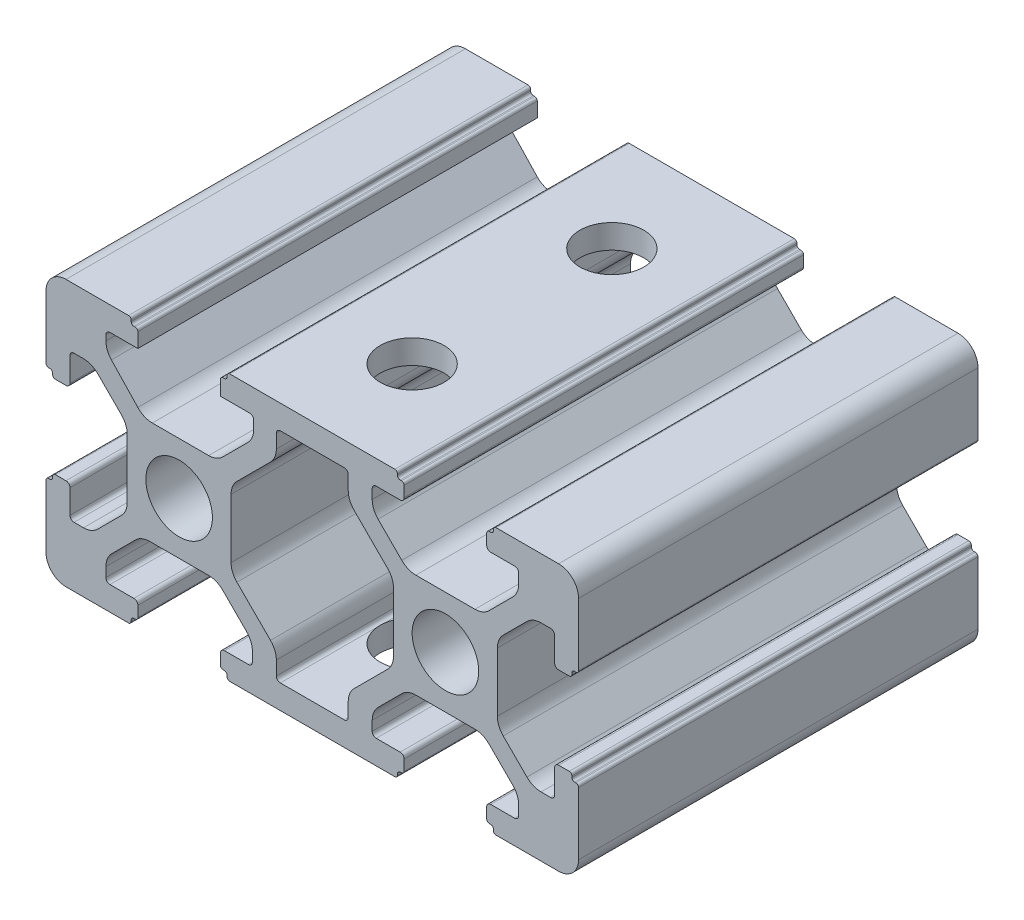
SolidWorks part; units mm, degrees
material "6063-O"
ref_plane "Front Plane" through (0, 0, 0) normal (0, 0, 1) x (1, 0, 0)
ref_plane "Top Plane" through (0, 0, 0) normal (0, 1, 0) x (1, 0, 0)
ref_plane "Right Plane" through (0, 0, 0) normal (1, 0, 0) x (0, 0, -1)
sketch "Sketch1" plane through (0, 0, 0) normal (0, 0, 1) x (1, 0, 0)
  line L0 (1.5, 0) -> (6.2, 0)
  line L1 (40, 1.5) -> (40, 6.2)
  line L2 (38.5, 20) -> (33.8, 20)
  line L3 (0, 18.5) -> (0, 13.8)
  line L4 (17.6, 1.8) -> (22.4, 1.8)
  line L5 (32.218, 13.9) -> (27.782, 13.9)
  line L6 (26.1, 12.218) -> (26.1, 7.782)
  line L7 (17.6, 18.2) -> (22.4, 18.2)
  line L8 (12.218, 13.9) -> (7.9864, 13.9)
  line L9 (6.1, 12.218) -> (6.1, 7.782)
  line L10 (7.782, 6.1) -> (12.218, 6.1)
  line L11 (13.9, 7.782) -> (13.9, 12.218)
  line L12 (27.782, 6.1) -> (32.218, 6.1)
  line L13 (33.9, 7.782) -> (33.9, 12.218)
  line L14 (26.7213, 14.3393) -> (24.9393, 16.1213)
  line L15 (33.2787, 14.3393) -> (35.0607, 16.1213)
  line L16 (34.3393, 13.2787) -> (36.1213, 15.0607)
  line L17 (25.6607, 6.7213) -> (23.1393, 4.2)
  line L18 (15.2, 1.8) -> (13.4, 1.8)
  line L19 (26.7213, 5.6607) -> (24.9393, 3.8787)
  line L20 (24.8, 1.8) -> (26.6, 1.8)
  line L21 (15.3, 18.2) -> (13.1, 18.2)
  line L22 (13.2787, 14.3393) -> (15.1607, 16.2213)
  line L23 (14.3393, 13.2787) -> (16.8607, 15.8)
  line L24 (5.6607, 6.7213) -> (3.8787, 4.9393)
  line L25 (6.7213, 5.6607) -> (4.9393, 3.8787)
  line L26 (6.897, 14.3689) -> (4.9106, 16.4674)
  line L27 (5.6607, 13.2787) -> (3.8787, 15.0607)
  line L28 (14.3393, 6.7213) -> (16.8607, 4.2)
  line L29 (13.2787, 5.6607) -> (15.0607, 3.8787)
  line L30 (24.8, 18.2) -> (26.6, 18.2)
  line L31 (25.6607, 13.2787) -> (23.1393, 15.8)
  line L32 (34.3393, 6.7213) -> (36.1213, 4.9393)
  line L33 (33.2787, 5.6607) -> (35.0607, 3.8787)
  line L34 (1.8, 15.2) -> (1.8, 13.4)
  line L35 (24.5, 2.1) -> (24.5, 2.818)
  line L36 (4.5, 2.1) -> (4.5, 2.818)
  line L37 (2.818, 4.5) -> (2.1, 4.5)
  line L38 (4.5, 17.9) -> (4.5, 17.4986)
  line L39 (2.818, 15.5) -> (2.1, 15.5)
  line L40 (15.6, 17.9) -> (15.6, 17.282)
  line L41 (15.5, 2.818) -> (15.5, 2.1)
  line L42 (38.2, 15.2) -> (38.2, 13.4)
  line L43 (35.5, 2.818) -> (35.5, 2.1)
  line L44 (37.182, 4.5) -> (37.9, 4.5)
  line L45 (35.5, 17.182) -> (35.5, 17.9)
  line L46 (37.182, 15.5) -> (37.9, 15.5)
  line L47 (17.3, 2.1) -> (17.3, 3.1393)
  line L48 (22.7, 2.1) -> (22.7, 3.1393)
  line L49 (17.3, 17.9) -> (17.3, 16.8607)
  line L50 (22.7, 17.9) -> (22.7, 16.8607)
  line L51 (24.5, 17.9) -> (24.5, 17.182)
  line L52 (6.9, 19.3) -> (6.9, 18.2)
  line L53 (13.1, 19.3) -> (13.1, 18.2)
  line L54 (6.9, 1.5) -> (6.9, 0.7)
  line L55 (13.1, 1.5) -> (13.1, 0.7)
  line L56 (13.8, 0) -> (26.2, 0)
  line L57 (6.6, 1.8) -> (4.8, 1.8)
  line L58 (6.9, 18.2) -> (4.8, 18.2)
  line L59 (6.2, 20) -> (1.5, 20)
  line L60 (39.3, 6.9) -> (38.5, 6.9)
  line L61 (39.3, 13.1) -> (38.5, 13.1)
  line L62 (1.5, 13.1) -> (0.7, 13.1)
  line L63 (1.5, 6.9) -> (0.7, 6.9)
  line L64 (0, 6.2) -> (0, 1.5)
  line L65 (1.8, 6.6) -> (1.8, 4.8)
  line L66 (38.2, 6.6) -> (38.2, 4.8)
  line L67 (40, 13.8) -> (40, 18.5)
  line L68 (33.1, 19.3) -> (33.1, 18.5)
  line L69 (26.9, 19.3) -> (26.9, 18.5)
  line L70 (26.9, 1.5) -> (26.9, 0.7)
  line L71 (33.1, 1.5) -> (33.1, 0.7)
  line L72 (33.8, 0) -> (38.5, 0)
  line L73 (33.4, 1.8) -> (35.2, 1.8)
  line L74 (26.2, 20) -> (13.8, 20)
  line L75 (33.4, 18.2) -> (35.2, 18.2)
  line L76 (6.7, 0.5) -> (6.6, 0.5)
  line L77 (6.4, 0.3) -> (6.4, 0.2)
  line L78 (13.3, 0.5) -> (13.4, 0.5)
  line L79 (13.6, 0.3) -> (13.6, 0.2)
  line L80 (26.7, 0.5) -> (26.6, 0.5)
  line L81 (26.4, 0.3) -> (26.4, 0.2)
  line L82 (33.3, 0.5) -> (33.4, 0.5)
  line L83 (33.6, 0.3) -> (33.6, 0.2)
  line L85 (6.4, 19.8) -> (6.4, 19.7)
  line L86 (6.6, 19.5) -> (6.7, 19.5)
  line L87 (13.6, 19.8) -> (13.6, 19.7)
  line L88 (13.4, 19.5) -> (13.3, 19.5)
  line L89 (26.4, 19.8) -> (26.4, 19.7)
  line L90 (26.6, 19.5) -> (26.7, 19.5)
  line L91 (33.6, 19.8) -> (33.6, 19.7)
  line L92 (33.4, 19.5) -> (33.3, 19.5)
  line L93 (0.5, 13.3) -> (0.5, 13.4)
  line L94 (0.3, 13.6) -> (0.2, 13.6)
  line L95 (0.5, 6.7) -> (0.5, 6.6)
  line L96 (0.3, 6.4) -> (0.2, 6.4)
  line L97 (39.5, 13.3) -> (39.5, 13.4)
  line L98 (39.7, 13.6) -> (39.8, 13.6)
  line L99 (39.5, 6.7) -> (39.5, 6.6)
  line L100 (39.7, 6.4) -> (39.8, 6.4)
  circle A0 centre (10, 10) radius 2.5
  circle A1 centre (30, 10) radius 2.5
  arc A2 (38.5, 0) -> (40, 1.5) centre (38.5, 1.5) ccw
  arc A3 (40, 18.5) -> (38.5, 20) centre (38.5, 18.5) ccw
  arc A4 (1.5, 0) -> (0, 1.5) centre (1.5, 1.5) cw
  arc A5 (1.5, 20) -> (0, 18.5) centre (1.5, 18.5) ccw
  arc A6 (26.7213, 5.6607) -> (27.782, 6.1) centre (27.782, 4.6) cw
  arc A7 (32.218, 6.1) -> (33.2787, 5.6607) centre (32.218, 4.6) cw
  arc A8 (33.9, 7.782) -> (34.3393, 6.7213) centre (35.4, 7.782) ccw
  arc A9 (33.2787, 14.3393) -> (32.218, 13.9) centre (32.218, 15.4) cw
  arc A10 (14.3393, 6.7213) -> (13.9, 7.782) centre (15.4, 7.782) cw
  arc A11 (14.3393, 13.2787) -> (13.9, 12.218) centre (15.4, 12.218) ccw
  arc A12 (25.6607, 6.7213) -> (26.1, 7.782) centre (24.6, 7.782) ccw
  arc A13 (26.1, 12.218) -> (25.6607, 13.2787) centre (24.6, 12.218) ccw
  arc A14 (27.782, 13.9) -> (26.7213, 14.3393) centre (27.782, 15.4) cw
  arc A15 (5.6607, 13.2787) -> (6.1, 12.218) centre (4.6, 12.218) cw
  arc A16 (5.6607, 6.7213) -> (6.1, 7.782) centre (4.6, 7.782) ccw
  arc A17 (13.2787, 5.6607) -> (12.218, 6.1) centre (12.218, 4.6) ccw
  arc A18 (6.7213, 5.6607) -> (7.782, 6.1) centre (7.782, 4.6) cw
  arc A19 (13.2787, 14.3393) -> (12.218, 13.9) centre (12.218, 15.4) cw
  arc A20 (6.897, 14.3689) -> (7.9864, 13.9) centre (7.9864, 15.4) ccw
  arc A21 (36.1213, 4.9393) -> (37.182, 4.5) centre (37.182, 6) ccw
  arc A22 (36.1213, 15.0607) -> (37.182, 15.5) centre (37.182, 14) cw
  arc A23 (35.0607, 16.1213) -> (35.5, 17.182) centre (34, 17.182) ccw
  arc A24 (24.5, 17.182) -> (24.9393, 16.1213) centre (26, 17.182) ccw
  arc A25 (22.7, 16.8607) -> (23.1393, 15.8) centre (24.2, 16.8607) ccw
  arc A26 (17.3, 16.8607) -> (16.8607, 15.8) centre (15.8, 16.8607) cw
  arc A27 (4.9106, 16.4674) -> (4.5, 17.4986) centre (6, 17.4986) cw
  arc A28 (15.6, 17.282) -> (15.1607, 16.2213) centre (14.1, 17.282) cw
  arc A29 (3.8787, 15.0607) -> (2.818, 15.5) centre (2.818, 14) ccw
  arc A30 (3.8787, 4.9393) -> (2.818, 4.5) centre (2.818, 6) cw
  arc A31 (4.9393, 3.8787) -> (4.5, 2.818) centre (6, 2.818) ccw
  arc A32 (35.0607, 3.8787) -> (35.5, 2.818) centre (34, 2.818) cw
  arc A33 (24.9393, 3.8787) -> (24.5, 2.818) centre (26, 2.818) ccw
  arc A34 (22.7, 3.1393) -> (23.1393, 4.2) centre (24.2, 3.1393) cw
  arc A35 (17.3, 3.1393) -> (16.8607, 4.2) centre (15.8, 3.1393) ccw
  arc A36 (15.5, 2.818) -> (15.0607, 3.8787) centre (14, 2.818) ccw
  arc A37 (1.8, 6.6) -> (1.5, 6.9) centre (1.5, 6.6) ccw
  arc A38 (1.8, 13.4) -> (1.5, 13.1) centre (1.5, 13.4) cw
  arc A39 (17.6, 18.2) -> (17.3, 17.9) centre (17.6, 17.9) ccw
  arc A40 (22.4, 1.8) -> (22.7, 2.1) centre (22.4, 2.1) ccw
  arc A41 (17.6, 1.8) -> (17.3, 2.1) centre (17.6, 2.1) cw
  arc A42 (15.2, 1.8) -> (15.5, 2.1) centre (15.2, 2.1) ccw
  arc A43 (6.6, 1.8) -> (6.9, 1.5) centre (6.6, 1.5) cw
  arc A44 (13.4, 1.8) -> (13.1, 1.5) centre (13.4, 1.5) ccw
  arc A45 (24.8, 1.8) -> (24.5, 2.1) centre (24.8, 2.1) cw
  arc A46 (35.2, 1.8) -> (35.5, 2.1) centre (35.2, 2.1) ccw
  arc A47 (26.6, 1.8) -> (26.9, 1.5) centre (26.6, 1.5) cw
  arc A48 (33.4, 1.8) -> (33.1, 1.5) centre (33.4, 1.5) ccw
  arc A49 (26.9, 18.5) -> (26.6, 18.2) centre (26.6, 18.5) cw
  arc A50 (33.1, 18.5) -> (33.4, 18.2) centre (33.4, 18.5) ccw
  arc A51 (37.9, 4.5) -> (38.2, 4.8) centre (37.9, 4.8) ccw
  arc A52 (38.5, 13.1) -> (38.2, 13.4) centre (38.5, 13.4) cw
  arc A53 (38.5, 6.9) -> (38.2, 6.6) centre (38.5, 6.6) ccw
  arc A54 (38.2, 15.2) -> (37.9, 15.5) centre (37.9, 15.2) ccw
  arc A55 (35.2, 18.2) -> (35.5, 17.9) centre (35.2, 17.9) cw
  arc A56 (24.8, 18.2) -> (24.5, 17.9) centre (24.8, 17.9) ccw
  arc A57 (22.4, 18.2) -> (22.7, 17.9) centre (22.4, 17.9) cw
  arc A58 (15.3, 18.2) -> (15.6, 17.9) centre (15.3, 17.9) cw
  arc A59 (4.5, 17.9) -> (4.8, 18.2) centre (4.8, 17.9) cw
  arc A60 (1.8, 15.2) -> (2.1, 15.5) centre (2.1, 15.2) cw
  arc A61 (1.8, 4.8) -> (2.1, 4.5) centre (2.1, 4.8) ccw
  arc A62 (4.5, 2.1) -> (4.8, 1.8) centre (4.8, 2.1) ccw
  arc A63 (34.3393, 13.2787) -> (33.9, 12.218) centre (35.4, 12.218) ccw
  arc A64 (6.4, 0.2) -> (6.2, 0) centre (6.2, 0.2) cw
  arc A65 (6.6, 0.5) -> (6.4, 0.3) centre (6.6, 0.3) ccw
  arc A66 (6.7, 0.5) -> (6.9, 0.7) centre (6.7, 0.7) ccw
  arc A67 (13.6, 0.2) -> (13.8, 0) centre (13.8, 0.2) ccw
  arc A68 (13.4, 0.5) -> (13.6, 0.3) centre (13.4, 0.3) cw
  arc A69 (13.3, 0.5) -> (13.1, 0.7) centre (13.3, 0.7) cw
  arc A70 (26.4, 0.2) -> (26.2, 0) centre (26.2, 0.2) cw
  arc A71 (26.6, 0.5) -> (26.4, 0.3) centre (26.6, 0.3) ccw
  arc A72 (26.7, 0.5) -> (26.9, 0.7) centre (26.7, 0.7) ccw
  arc A73 (33.6, 0.2) -> (33.8, 0) centre (33.8, 0.2) ccw
  arc A74 (33.4, 0.5) -> (33.6, 0.3) centre (33.4, 0.3) cw
  arc A75 (33.3, 0.5) -> (33.1, 0.7) centre (33.3, 0.7) cw
  arc A76 (39.8, 6.4) -> (40, 6.2) centre (39.8, 6.2) cw
  arc A77 (39.5, 6.6) -> (39.7, 6.4) centre (39.7, 6.6) ccw
  arc A78 (39.5, 6.7) -> (39.3, 6.9) centre (39.3, 6.7) ccw
  arc A79 (39.5, 13.3) -> (39.3, 13.1) centre (39.3, 13.3) cw
  arc A80 (39.5, 13.4) -> (39.7, 13.6) centre (39.7, 13.4) cw
  arc A81 (39.8, 13.6) -> (40, 13.8) centre (39.8, 13.8) ccw
  arc A82 (33.3, 19.5) -> (33.1, 19.3) centre (33.3, 19.3) ccw
  arc A83 (33.6, 19.7) -> (33.4, 19.5) centre (33.4, 19.7) cw
  arc A84 (33.6, 19.8) -> (33.8, 20) centre (33.8, 19.8) cw
  arc A85 (26.7, 19.5) -> (26.9, 19.3) centre (26.7, 19.3) cw
  arc A86 (26.4, 19.7) -> (26.6, 19.5) centre (26.6, 19.7) ccw
  arc A87 (26.4, 19.8) -> (26.2, 20) centre (26.2, 19.8) ccw
  arc A88 (0.2, 6.4) -> (0, 6.2) centre (0.2, 6.2) ccw
  arc A89 (0.5, 6.6) -> (0.3, 6.4) centre (0.3, 6.6) cw
  arc A90 (0.5, 6.7) -> (0.7, 6.9) centre (0.7, 6.7) cw
  arc A91 (13.3, 19.5) -> (13.1, 19.3) centre (13.3, 19.3) ccw
  arc A92 (13.6, 19.7) -> (13.4, 19.5) centre (13.4, 19.7) cw
  arc A93 (13.6, 19.8) -> (13.8, 20) centre (13.8, 19.8) cw
  arc A94 (6.2, 20) -> (6.4, 19.8) centre (6.2, 19.8) cw
  arc A95 (6.7, 19.5) -> (6.9, 19.3) centre (6.7, 19.3) cw
  arc A96 (6.4, 19.7) -> (6.6, 19.5) centre (6.6, 19.7) ccw
  arc A97 (0.5, 13.3) -> (0.7, 13.1) centre (0.7, 13.3) ccw
  arc A98 (0.2, 13.6) -> (0, 13.8) centre (0.2, 13.8) cw
  arc A99 (0.5, 13.4) -> (0.3, 13.6) centre (0.3, 13.4) ccw
  point P87 (0, 0)
  point P178 (1.8, 6.9)
  point P181 (1.8, 13.1)
  point P186 (22.7, 1.8)
  point P193 (6.9, 1.8)
  point P204 (33.1, 1.8)
  point P209 (33.1, 18.2)
  point P216 (38.2, 6.9)
  point P243 (6.9, 0.5)
  point P248 (13.6, 0.5)
  point P257 (26.9, 0.5)
extrude "Boss-Extrude2" add sketch "Sketch1" along normal blind 30 contours A57 L7 A39 L49 A26 L23 A11 L11 A10 L28 A35 L47 A41 L4 A40 L48 A34 L17 A12 L6 A13 L31 A25 L50 | A0 | A1 | L59 A5 L3 A98 L94 A99 L93 A97 L62 A38 L34 A60 L39 A29 L27 A15 L9 A16 L24 A30 L37 A61 L65 A37 L63 A90 L95 A89 L96 A88 L64 A4 L0 A64 L77 A65 L76 A66 L54 A43 L57 A62 L36 A31 L25 A18 L10 A17 L29 A36 L41 A42 L18 A44 L55 A69 L78 A68 L79 A67 L56 A70 L81 A71 L80 A72 L70 A47 L20 A45 L35 A33 L19 A6 L12 A7 L33 A32 L43 A46 L73 A48 L71 A75 L82 A74 L83 A73 L72 A2 L1 A76 L100 A77 L99 A78 L60 A53 L66 A51 L44 A21 L32 A8 L13 A63 L16 A22 L46 A54 L42 A52 L61 A79 L97 A80 L98 A81 L67 A3 L2 A84 L91 A83 L92 A82 L68 A50 L75 A55 L45 A23 L15 A9 L5 A14 L14 A24 L51 A56 L30 A49 L69 A85 L90 A86 L89 A87 L74 A93 L87 A92 L88 A91 L53 L21 A58 L40 A28 L22 A19 L8 A20 L26 A27 L38 A59 L58 L52 A95 L86 A96 L85 A94
sketch "Sketch2" plane through (0, 20, 0) normal (0, 1, 0) x (1, 0, 0)
  line L0 (26.2, 0) -> (13.8, 0) construction
  circle A0 centre (20, -7.5) radius 2.4
  circle A1 centre (20, -22.5) radius 2.4
  point P4 (0, 0)
  point P5 (20, 0)
  point P10 (20.1626, -24.9265)
  dimension "D1" = 4.8
  dimension "D2" = 7.5
  dimension "D3" = 15
extrude "Cut-Extrude1" cut sketch "Sketch2" against normal blind 28
sketch "Sketch4" plane through (6.1, 0, 0) normal (-1, 0, 0) x (0, 0, 1)
  line L0 (0, 12.218) -> (0, 7.782) construction
  circle A0 centre (17, 10) radius 1.45
  point P2 (0, 0)
  point P5 (0, 10)
  dimension "D1" = 2.9
  dimension "D2" = 17
extrude "Cut-Extrude2" cut sketch "Sketch4" against normal blind 70
